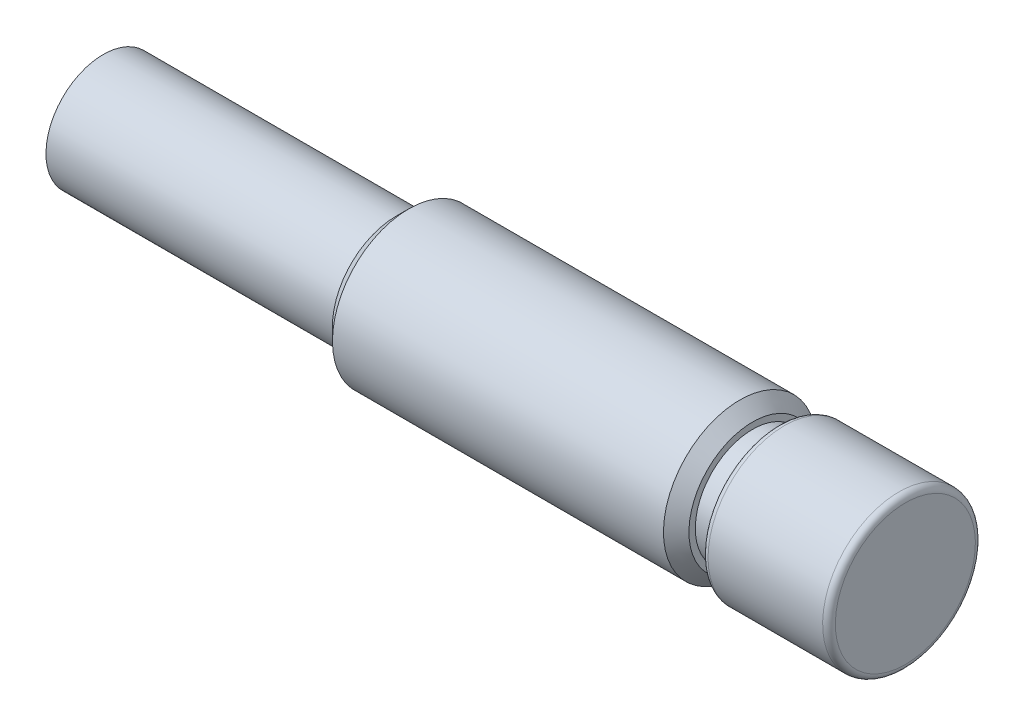
SolidWorks part; units mm, degrees
ref_plane "Plano frontal" through (0, 0, 0) normal (0, 0, 1) x (1, 0, 0)
ref_plane "Plano superior" through (0, 0, 0) normal (0, 1, 0) x (1, 0, 0)
ref_plane "Plano direito" through (0, 0, 0) normal (1, 0, 0) x (0, 0, -1)
sketch "Esboço1" plane through (0, 0, 0) normal (0, 0, 1) x (1, 0, 0)
  line L0 (3.3998, 0) -> (63, 0)
  line L1 (63, 0) -> (63, 6)
  line L2 (63, 6) -> (53, 6)
  line L3 (53, 6) -> (53, 4.5)
  line L4 (53, 4.5) -> (51, 4.5)
  line L5 (51, 4.5) -> (51, 6)
  line L6 (51, 6) -> (23, 6)
  line L7 (23, 6) -> (23, 4.5)
  line L8 (23, 4.5) -> (0, 4.5)
  line L11 (0, 4.5) -> (0, 4.3564)
  line L12 (0, 4.3564) -> (3.3998, 0)
  point P0 (11.5, 4.5)
  point P17 (52, 4.5)
  point P18 (37, 6)
  point P19 (58, 6)
  dimension "D1" = 4.5
  dimension "D2" = 6
  dimension "D3" = 23
  dimension "D4" = 3.3998
  dimension "D5" = 63
  dimension "D6" = 2
  dimension "D7" = 10
  dimension "D8" = 4.5
  dimension "D10" = 1.5
revolve "Revolução1" add sketch "Esboço1" angle 360 about L0
cosmetic thread "Representação de rosca2" parameters "D2"=10.072
cosmetic thread "Representação de rosca3" parameters "D2"=10.619
cosmetic thread "Representação de rosca4" parameters "D2"=6.619
fillet "Filete1" radius 0.5 2 edges at (63, -6, 0) (53, -6, 0)
chamfer "Chanfro1" distance 1 angle 45 2 edges at (51, -6, 0) (23, -6, 0)
